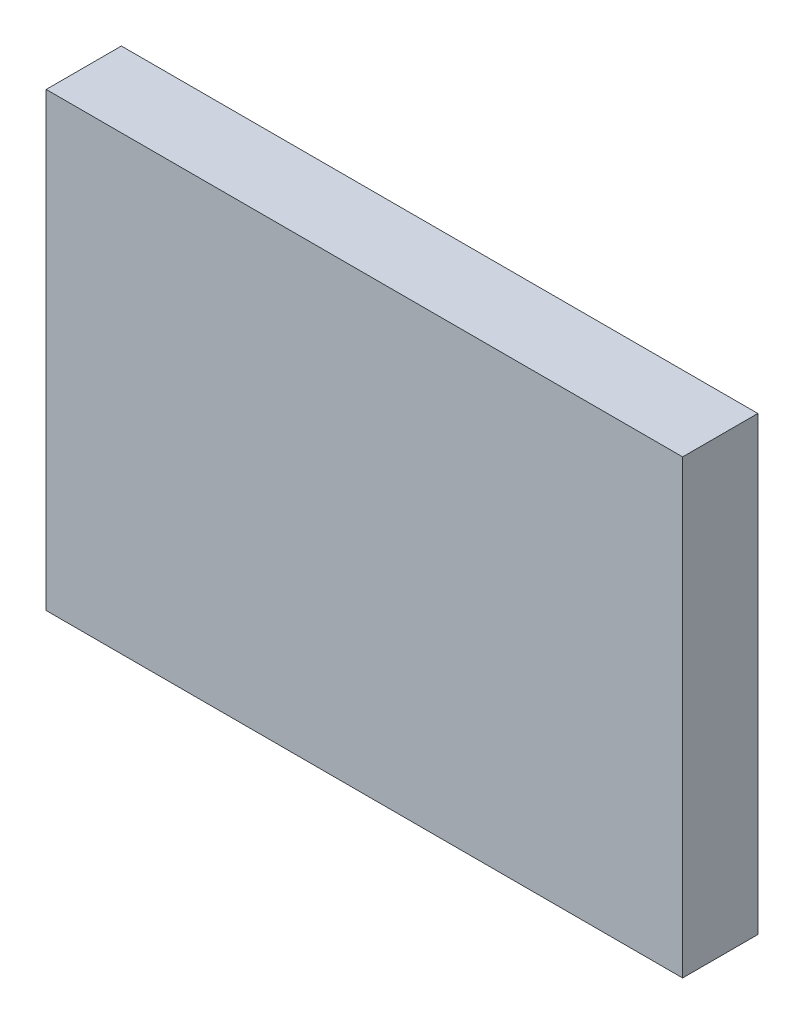
SolidWorks part; units mm, degrees
ref_plane "Plan de face" through (0, 0, 0) normal (0, 0, 1) x (1, 0, 0)
ref_plane "Plan de dessus" through (0, 0, 0) normal (0, 1, 0) x (1, 0, 0)
ref_plane "Plan de droite" through (0, 0, 0) normal (1, 0, 0) x (0, 0, -1)
sketch "Esquisse1" plane through (0, 0, 0) normal (0, 0, 1) x (1, 0, 0)
  line L1 (0, 0) -> (110, 0)
  line L2 (0, 0) -> (0, 78)
  line L3 (0, 78) -> (110, 78)
  line L4 (110, 0) -> (110, 78)
  dimension "D1" = 110
  dimension "D2" = 78
extrude "Boss.-Extru.1" add sketch "Esquisse1" along normal blind 13
